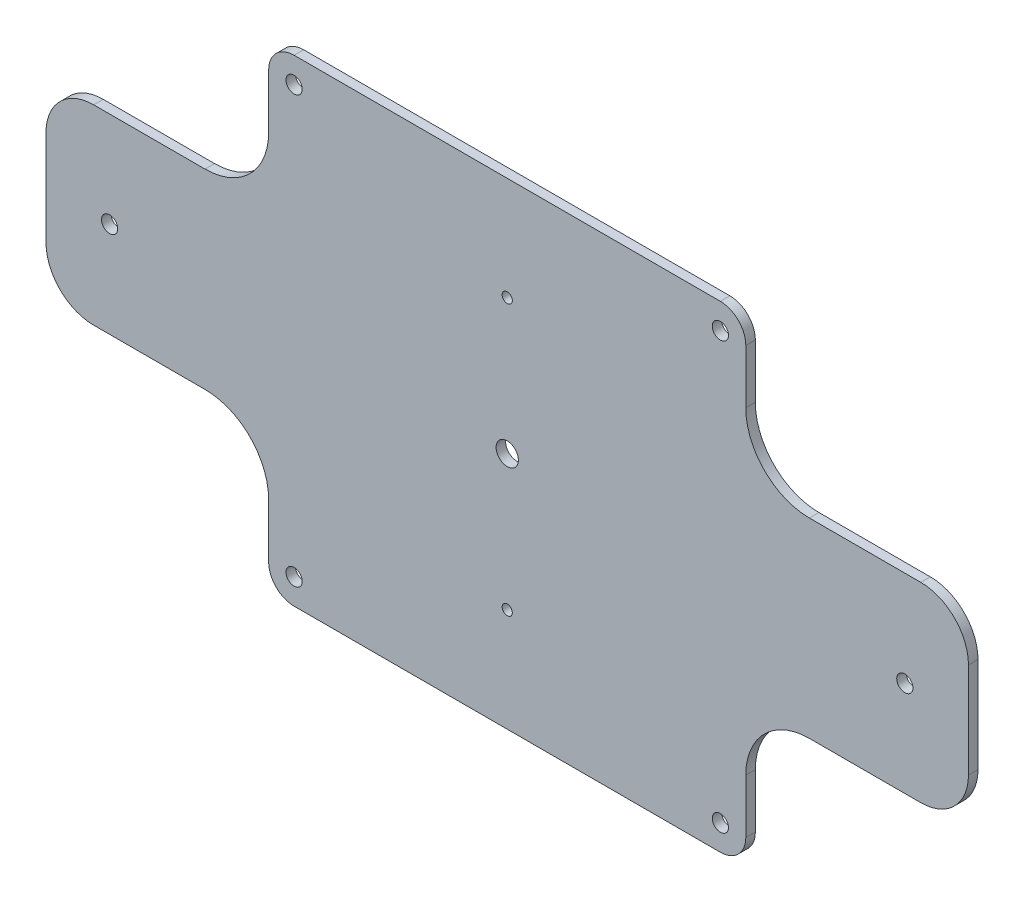
SolidWorks part; units mm, degrees
ref_plane "前视基准面" through (0, 0, 0) normal (0, 0, 1) x (1, 0, 0)
ref_plane "上视基准面" through (0, 0, 0) normal (0, 1, 0) x (1, 0, 0)
ref_plane "右视基准面" through (0, 0, 0) normal (1, 0, 0) x (0, 0, -1)
sketch "草图1" plane through (0, 0, 0) normal (0, 0, 1) x (1, 0, 0)
  line L1 (-75, 75) -> (75, 75)
  line L2 (-75, 75) -> (-75, -75)
  line L3 (-75, -75) -> (75, -75)
  line L4 (75, 75) -> (75, -75)
  line L5 (0, -75) -> (0, 75) construction
  line L6 (-75, 0) -> (75, 0) construction
  point P0 (0, 0)
  dimension "D1" = 150
  dimension "D2" = 150
extrude "凸台-拉伸1" add sketch "草图1" along normal blind 3
sketch "草图2" plane through (0, 0, 3) normal (0, 0, 1) x (1, 0, 0)
  line L1 (-20, 20) -> (20, 20) construction
  line L2 (-20, 20) -> (-20, -20) construction
  line L3 (-20, -20) -> (20, -20) construction
  line L4 (20, 20) -> (20, -20) construction
  line L5 (0, -20) -> (0, 20) construction
  line L6 (-20, 0) -> (20, 0) construction
  circle A0 centre (-20, 20) radius 1.75
  circle A1 centre (20, 20) radius 1.75
  circle A2 centre (20, -20) radius 1.75
  circle A3 centre (-20, -20) radius 1.75
  point P0 (0, 0)
  dimension "D2" = 3.5
  dimension "D1" = 40
extrude "切除-拉伸1" [suppressed] cut sketch "草图2" against normal through all
sketch "草图3" plane through (0, 0, 3) normal (0, 0, 1) x (1, 0, 0)
  line L0 (-75, -75) -> (75, -75) construction
  line L1 (46, 25) -> (-46, 25) construction
  line L2 (46, 25) -> (46, -45) construction
  line L3 (46, -45) -> (-46, -45) construction
  line L4 (-46, 25) -> (-46, -45) construction
  line L5 (0, -45) -> (0, 25) construction
  line L6 (46, -10) -> (-46, -10) construction
  circle A0 centre (46, 25) radius 1.75
  circle A1 centre (46, -45) radius 1.75
  circle A2 centre (-46, -45) radius 1.75
  circle A3 centre (-46, 25) radius 1.75
  point P0 (0, -10)
  dimension "D4" = 3.5
  dimension "D1" = 70
  dimension "D2" = 92
  dimension "D3" = 30
extrude "切除-拉伸2" [suppressed] cut sketch "草图3" against normal through all
sketch "草图4" plane through (0, 0, 3) normal (0, 0, 1) x (1, 0, 0)
  line L4 (75, -75) -> (75, 75) construction
  line L5 (-67, 67) -> (67, 67) construction
  line L6 (-67, 67) -> (-67, -67) construction
  line L7 (-67, -67) -> (67, -67) construction
  line L12 (67, 67) -> (67, -67) construction
  line L13 (0, -67) -> (0, 67) construction
  line L14 (-67, 0) -> (67, 0) construction
  line L15 (75, 75) -> (-75, 75) construction
  circle A4 centre (-67, 67) radius 2.55
  circle A5 centre (-67, -67) radius 2.55
  circle A6 centre (67, -67) radius 2.55
  circle A7 centre (67, 67) radius 2.55
  circle A8 centre (0, 0) radius 3.5
  point P0 (0, 0)
  dimension "D3" = 5.1
  dimension "D4" = 7
  dimension "D1" = 8
  dimension "D2" = 8
extrude "切除-拉伸3" cut sketch "草图4" against normal blind 7
fillet "圆角1" radius 8 4 edges at (-75, -75, 1.5) (75, -75, 1.5) (75, 75, 1.5) (-75, 75, 1.5)
sketch "草图5" plane through (0, 0, 3) normal (0, 0, 1) x (1, 0, 0)
  line L0 (-10, 60) -> (10, 60) construction
  line L1 (-10, 61.6) -> (10, 61.6)
  line L2 (-10, 58.4) -> (10, 58.4)
  line L3 (0, 75) -> (0, 60) construction
  line L4 (67, 75) -> (-67, 75) construction
  arc A0 (-10, 61.6) -> (-10, 58.4) centre (-10, 60) ccw
  arc A1 (10, 58.4) -> (10, 61.6) centre (10, 60) ccw
  point P2 (0, 60)
  dimension "D1" = 1.6
  dimension "D2" = 15
  dimension "20" = 20
extrude "切除-拉伸4" [suppressed] cut sketch "草图5" against normal blind 7
sketch "草图6" plane through (0, 0, 3) normal (0, 0, 1) x (1, 0, 0)
  line L0 (15.9475, 0) -> (133.4351, 0) construction
  line L1 (-75, 67) -> (-75, -67) construction
  line L2 (-145, -30) -> (-75, -30)
  line L3 (-145, -30) -> (-145, 30)
  line L4 (-145, 30) -> (-75, 30)
  line L5 (-75, -30) -> (-75, 30)
  line L6 (-110, 30) -> (-110, -30) construction
  line L7 (-145, 0) -> (-75, 0) construction
  circle A0 centre (-125, 0) radius 2.55
  point P1 (-110, 0)
  dimension "D3" = 5.1
  dimension "D4" = 50
  dimension "D1" = 70
  dimension "D2" = 60
extrude "凸台-拉伸2" add sketch "草图6" against normal up to surface (3 mm away) up to face at (3.5, 0, 0)
mirror "镜向1" about plane through (0, 0, 0) normal (1, 0, 0) of "凸台-拉伸2"
fillet "圆角2" radius 20 4 edges at (-75, 30, 1.5) (75, 30, 1.5) (75, -30, 1.5) (-75, -30, 1.5)
fillet "圆角3" radius 15 4 edges at (-145, 30, 1.5) (145, -30, 1.5) (145, 30, 1.5) (-145, -30, 1.5)
sketch "草图7" plane through (0, 0, 3) normal (0, 0, 1) x (1, 0, 0)
  line L0 (0, 75) -> (0, -82.0421) construction
  line L1 (67, 75) -> (-67, 75) construction
  circle A0 centre (0, 42.5) radius 1.6
  circle A1 centre (0, -42.5) radius 1.6
  circle A2 centre (0, 0) radius 3.5 construction
  dimension "D1" = 3.2
  dimension "D2" = 42.5
  dimension "D3" = 42.5
extrude "切除-拉伸5" cut sketch "草图7" against normal blind 10
